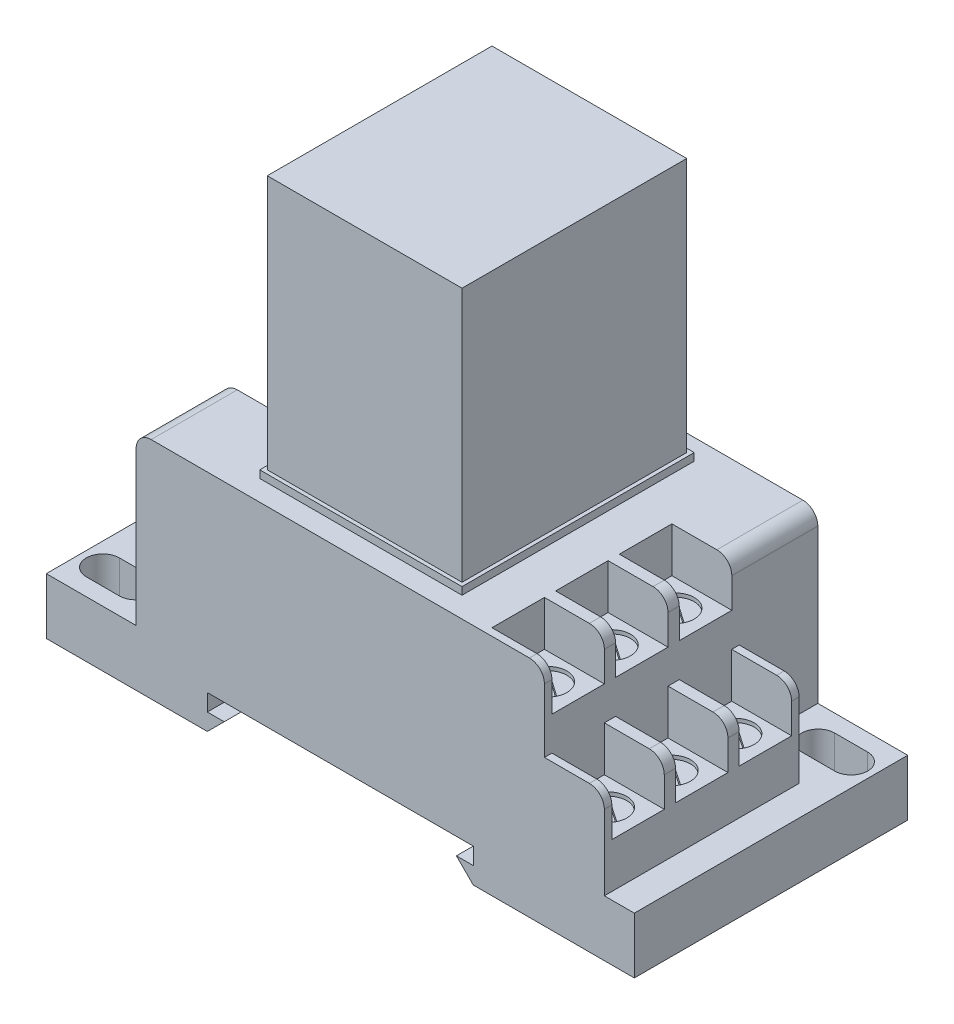
SolidWorks part; units mm, degrees
ref_plane "Спереди" through (0, 0, 0) normal (0, 0, 1) x (1, 0, 0)
ref_plane "Сверху" through (0, 0, 0) normal (0, 1, 0) x (1, 0, 0)
ref_plane "Справа" through (0, 0, 0) normal (1, 0, 0) x (0, 0, -1)
sketch "Эскиз1" plane through (0, 0, 0) normal (0, 1, 0) x (1, 0, 0)
  line L1 (0, 0) -> (78.5, 0)
  line L2 (0, 0) -> (0, 36.5)
  line L3 (0, 36.5) -> (78.5, 36.5)
  line L4 (78.5, 0) -> (78.5, 36.5)
  dimension "D1" = 36.5
  dimension "D2" = 78.5
extrude "Бобышка-Вытянуть1" add sketch "Эскиз1" along normal blind 30
sketch "Эскиз2" plane through (0, 0, 0) normal (0, 0, 1) x (1, 0, 0)
  line L0 (39.25, 30) -> (39.25, 0) construction
  line L1 (21.5, 4.5) -> (57, 4.5)
  line L2 (21.5, 4.5) -> (21.5, 2.25)
  line L4 (0, 0) -> (78.5, 0) construction
  line L5 (57, 4.5) -> (57, 2.25)
  line L6 (21.5, 2.25) -> (23.75, 2.25)
  line L7 (23.75, 2.25) -> (21.5, 0)
  line L8 (0, 30) -> (78.5, 30) construction
  line L9 (54.75, 2.25) -> (57, 0)
  line L10 (57, 2.25) -> (54.75, 2.25)
  line L11 (21.5, 0) -> (57, 0)
  dimension "D1" = 35.5
  dimension "D2" = 4.5
  dimension "D3" = 17.75
  dimension "D4" = 2.25
  dimension "D5" = 2.25
  dimension "D6" = 17.75
extrude "Вырез-Вытянуть1" cut sketch "Эскиз2" against normal through all
sketch "Эскиз3" plane through (0, 0, 0) normal (0, 0, 1) x (1, 0, 0)
  line L0 (0, 7.5) -> (12, 7.5)
  line L1 (0, 30) -> (0, 0) construction
  line L2 (12, 7.5) -> (12, 28)
  line L3 (0, 30) -> (78.5, 30) construction
  line L4 (14, 30) -> (64.5, 30)
  line L5 (66.5, 28) -> (66.5, 7.5)
  line L6 (66.5, 7.5) -> (78.5, 7.5)
  line L7 (78.5, 30) -> (78.5, 0) construction
  line L8 (78.5, 7.5) -> (78.5, 31.9767)
  line L9 (78.5, 31.9767) -> (0, 31.9767)
  line L10 (0, 31.9767) -> (0, 7.5)
  line L11 (0, 0) -> (21.5, 0) construction
  line L12 (57, 0) -> (78.5, 0) construction
  arc A0 (14, 30) -> (12, 28) centre (14, 28) ccw
  arc A1 (66.5, 28) -> (64.5, 30) centre (64.5, 28) ccw
  point P22 (12, 30)
  point P25 (66.5, 30)
  dimension "D5" = 2
  dimension "D6" = 2
  dimension "D1" = 7.5
  dimension "D2" = 12
  dimension "D3" = 7.5
  dimension "D4" = 12
extrude "Вырез-Вытянуть2" cut sketch "Эскиз3" against normal through all
sketch "Эскиз4" plane through (0, 0, 0) normal (0, 0, 1) x (1, 0, 0)
  line L1 (66.5, 28) -> (66.5, 7.5) construction
  line L2 (66.5, 7.5) -> (74.5, 7.5)
  line L3 (66.5, 7.5) -> (66.5, 19.5)
  line L4 (66.5, 19.5) -> (72.5, 19.5)
  line L6 (74.5, 7.5) -> (74.5, 17.5)
  line L7 (66.5, 7.5) -> (78.5, 7.5) construction
  arc A0 (74.5, 17.5) -> (72.5, 19.5) centre (72.5, 17.5) ccw
  point P10 (74.5, 19.5)
  dimension "D3" = 2
  dimension "D1" = 8
  dimension "D2" = 12
extrude "Бобышка-Вытянуть2" add sketch "Эскиз4" against normal blind 26 separate body
sketch "Эскиз6" plane through (0, 0, -36.5) normal (0, 0, -1) x (-1, 0, 0)
  line L0 (0, 7.5) -> (-12, 7.5) construction
  line L1 (-12, 7.5) -> (-4, 7.5)
  line L2 (-12, 7.5) -> (-12, 19.5)
  line L3 (-12, 19.5) -> (-6, 19.5)
  line L4 (-4, 7.5) -> (-4, 17.5)
  arc A0 (-4, 17.5) -> (-6, 19.5) centre (-6, 17.5) ccw
  point P8 (-4, 19.5)
  dimension "D3" = 2
  dimension "D1" = 8
  dimension "D2" = 12
extrude "Бобышка-Вытянуть6" add sketch "Эскиз6" against normal blind 26 separate body
sketch "Эскиз7" plane through (0, 7.5, 0) normal (0, 1, 0) x (1, 0, 0)
  line L0 (71.05, 32) -> (75.45, 32) construction
  line L1 (71.05, 34.2) -> (75.45, 34.2)
  line L2 (71.05, 29.8) -> (75.45, 29.8)
  line L3 (3.05, 4.5) -> (7.45, 4.5) construction
  line L4 (3.05, 6.7) -> (7.45, 6.7)
  line L5 (3.05, 2.3) -> (7.45, 2.3)
  line L6 (0, 18.25) -> (78.5, 18.25) construction
  line L7 (0, 36.5) -> (0, 0) construction
  line L8 (78.5, 36.5) -> (78.5, 0) construction
  line L9 (39.25, 36.5) -> (39.25, 0) construction
  line L10 (64.5, 36.5) -> (14, 36.5) construction
  line L11 (14, 0) -> (64.5, 0) construction
  arc A0 (71.05, 34.2) -> (71.05, 29.8) centre (71.05, 32) ccw
  arc A1 (75.45, 29.8) -> (75.45, 34.2) centre (75.45, 32) ccw
  arc A2 (3.05, 6.7) -> (3.05, 2.3) centre (3.05, 4.5) ccw
  arc A3 (7.45, 2.3) -> (7.45, 6.7) centre (7.45, 4.5) ccw
  point P2 (73.25, 32)
  point P7 (5.25, 4.5)
  dimension "D1" = 13.75
  dimension "D2" = 27.5
  dimension "D3" = 4.4
  dimension "D4" = 4.4
  dimension "D5" = 68
  dimension "D6" = 34
  dimension "D7" = 4.4
  dimension "D8" = 4.4
extrude "Вырез-Вытянуть3" cut sketch "Эскиз7" against normal up to next (7.5 mm away)
sketch "Эскиз8" plane through (0, 19.5, 0) normal (0, 1, 0) x (1, 0, 0)
  line L2 (4, 10.5) -> (4, 36.5) construction
  line L4 (6, 10.5) -> (12, 10.5) construction
  line L11 (4, 18.5) -> (12, 18.5)
  line L12 (4, 18.5) -> (4, 11.5)
  line L13 (4, 11.5) -> (12, 11.5)
  line L14 (12, 18.5) -> (12, 11.5)
  line L17 (4, 20) -> (12, 20)
  line L18 (4, 27) -> (4, 20)
  line L19 (4, 27) -> (12, 27)
  line L20 (12, 27) -> (12, 20)
  line L21 (4, 28.5) -> (12, 28.5)
  line L22 (4, 35.5) -> (4, 28.5)
  line L23 (4, 35.5) -> (12, 35.5)
  line L24 (12, 35.5) -> (12, 28.5)
  dimension "D1" = 1
  dimension "D2" = 3
  dimension "D3" = 7
  dimension "D4" = 8
  dimension "D5" = 8
extrude "Вырез-Вытянуть4" cut sketch "Эскиз8" against normal blind 6
sketch "Эскиз9" plane through (0, 19.5, 0) normal (0, 1, 0) x (1, 0, 0)
  line L0 (66.5, 26) -> (66.5, 0) construction
  line L1 (66.5, 25) -> (74.5, 25)
  line L2 (66.5, 25) -> (66.5, 18)
  line L3 (66.5, 18) -> (74.5, 18)
  line L4 (74.5, 25) -> (74.5, 18)
  line L5 (74.5, 26) -> (74.5, 0) construction
  line L6 (72.5, 26) -> (66.5, 26) construction
  line L7 (74.5, 16.5) -> (74.5, 9.5)
  line L8 (66.5, 16.5) -> (74.5, 16.5)
  line L9 (66.5, 16.5) -> (66.5, 9.5)
  line L10 (66.5, 9.5) -> (74.5, 9.5)
  line L11 (74.5, 8) -> (74.5, 1)
  line L12 (66.5, 8) -> (74.5, 8)
  line L21 (66.5, 8) -> (66.5, 1)
  line L22 (66.5, 1) -> (74.5, 1)
  dimension "D1" = 7
  dimension "D2" = 1
  dimension "D4" = 3
extrude "Вырез-Вытянуть5" cut sketch "Эскиз9" against normal blind 6
sketch "Эскиз10" plane through (0, 30, 0) normal (0, 1, 0) x (1, 0, 0)
  line L0 (39.25, 36.5) -> (39.25, 0) construction
  line L1 (64.5, 36.5) -> (14, 36.5) construction
  line L2 (14, 0) -> (64.5, 0) construction
  line L3 (14, 18.25) -> (64.5, 18.25) construction
  line L4 (14, 36.5) -> (14, 0) construction
  line L5 (64.5, 36.5) -> (64.5, 0) construction
  line L7 (25.75, 33.75) -> (52.75, 33.75)
  line L8 (25.75, 33.75) -> (25.75, 2.75)
  line L9 (25.75, 2.75) -> (52.75, 2.75)
  line L10 (52.75, 33.75) -> (52.75, 2.75)
  dimension "D1" = 27
  dimension "D2" = 13.5
  dimension "D3" = 31
  dimension "D4" = 15.5
extrude "Бобышка-Вытянуть7" add sketch "Эскиз10" along normal blind 35
sketch "Эскиз11" plane through (0, 65, 0) normal (0, 1, 0) x (1, 0, 0)
  line L0 (25.75, 33.75) -> (25.75, 2.75) construction
  line L1 (26.25, 33.25) -> (52.25, 33.25)
  line L2 (26.25, 33.25) -> (26.25, 3.25)
  line L3 (26.25, 3.25) -> (52.25, 3.25)
  line L4 (52.25, 33.25) -> (52.25, 3.25)
  line L5 (52.75, 33.75) -> (25.75, 33.75) construction
  line L6 (52.75, 2.75) -> (52.75, 33.75) construction
  line L7 (25.75, 2.75) -> (52.75, 2.75) construction
  line L9 (25.75, 33.75) -> (52.75, 33.75)
  line L10 (25.75, 33.75) -> (25.75, 2.75)
  line L11 (25.75, 2.75) -> (52.75, 2.75)
  line L12 (52.75, 33.75) -> (52.75, 2.75)
  dimension "D1" = 0.5
  dimension "D2" = 0.5
  dimension "D3" = 0.5
  dimension "D4" = 0.5
extrude "Вырез-Вытянуть6" cut sketch "Эскиз11" against normal blind 34
sketch "Эскиз12" plane through (0, 30, 0) normal (0, 1, 0) x (1, 0, 0)
  line L0 (12, 28.5) -> (12, 35.5) construction
  line L1 (12, 35.5) -> (20, 35.5)
  line L2 (12, 35.5) -> (12, 28.5)
  line L3 (12, 28.5) -> (20, 28.5)
  line L4 (20, 35.5) -> (20, 28.5)
  line L5 (64.5, 36.5) -> (14, 36.5) construction
  line L6 (12, 20) -> (20, 20)
  line L7 (12, 27) -> (20, 27)
  line L8 (20, 27) -> (20, 20)
  line L9 (12, 27) -> (12, 20)
  line L10 (12, 11.5) -> (20, 11.5)
  line L11 (12, 18.5) -> (20, 18.5)
  line L12 (20, 18.5) -> (20, 11.5)
  line L13 (12, 18.5) -> (12, 11.5)
  line L14 (58.5, 8) -> (66.5, 8)
  line L15 (58.5, 25.0174) -> (58.5, 18)
  line L16 (58.5, 1) -> (66.5, 1)
  line L17 (58.5, 8) -> (58.5, 1)
  line L18 (58.5, 25.0174) -> (66.5, 25.0174)
  line L19 (66.5, 16.5) -> (66.5, 9.5)
  line L20 (58.5, 16.5) -> (58.5, 9.5)
  line L21 (66.5, 25.0174) -> (66.5, 18)
  line L22 (66.5, 8) -> (66.5, 1)
  line L23 (58.5, 18) -> (66.5, 18)
  line L24 (58.5, 9.5) -> (66.5, 9.5)
  line L25 (58.5, 16.5) -> (66.5, 16.5)
  line L26 (14, 0) -> (64.5, 0) construction
  line L27 (66.5, 36.5) -> (66.5, 0) construction
  dimension "D1" = 7
  dimension "D2" = 8
  dimension "D3" = 8
  dimension "D4" = 1
  dimension "D6" = 1
  dimension "D7" = 8
  dimension "D8" = 8
  dimension "D9" = 8
  dimension "D10" = 8
  dimension "D11" = 8
  dimension "D12" = 7
  dimension "D13" = 7
  dimension "D14" = 1.5
  dimension "D15" = 1.5
  dimension "D5" = 3
extrude "Вырез-Вытянуть7" cut sketch "Эскиз12" against normal blind 6
sketch "Эскиз13" plane through (0, 13.5, 0) normal (0, 1, 0) x (1, 0, 0)
  line L0 (4, 35.5) -> (4, 28.5) construction
  line L1 (12, 35.5) -> (4, 35.5) construction
  line L2 (66.5, 1) -> (74.5, 1) construction
  line L3 (74.5, 1) -> (74.5, 8) construction
  line L4 (74.5, 9.5) -> (74.5, 16.5) construction
  line L5 (66.5, 9.5) -> (74.5, 9.5) construction
  line L6 (66.5, 18) -> (74.5, 18) construction
  line L7 (74.5, 18) -> (74.5, 25) construction
  circle A0 centre (8, 32) radius 2.5
  circle A1 centre (8, 23.5) radius 2.5
  circle A2 centre (8, 15) radius 2.5
  circle A3 centre (70.5, 4.5) radius 2.5
  circle A4 centre (70.5, 21.5) radius 2.5
  circle A5 centre (70.5, 13) radius 2.5
  dimension "D1" = 4
  dimension "D2" = 3.5
  dimension "D3" = 5
  dimension "D5" = 5
  dimension "D6" = 3.5
  dimension "D7" = 4
  dimension "D8" = 4
  dimension "D9" = 3.5
  dimension "D10" = 3.5
  dimension "D11" = 4
  dimension "D4" = 3
extrude "Вырез-Вытянуть8" cut sketch "Эскиз13" against normal blind 1
sketch "Эскиз14" plane through (0, 12.5, 0) normal (0, 1, 0) x (1, 0, 0)
  line L0 (68.1956, 5.4693) -> (72.2402, 2.7051)
  line L1 (68.7598, 6.2949) -> (72.8044, 3.5307)
  line L2 (68.7598, 14.7949) -> (72.8044, 12.0307)
  line L3 (68.1956, 13.9693) -> (72.2402, 11.2051)
  line L4 (68.7598, 23.2949) -> (72.8044, 20.5307)
  line L5 (68.1956, 22.4693) -> (72.2402, 19.7051)
  line L6 (5.6956, 24.4693) -> (9.7402, 21.7051)
  line L7 (6.2598, 16.7949) -> (10.3044, 14.0307)
  line L8 (6.2598, 25.2949) -> (10.3044, 22.5307)
  line L9 (5.6956, 32.9693) -> (9.7402, 30.2051)
  line L10 (5.6956, 15.9693) -> (9.7402, 13.2051)
  line L11 (6.2598, 33.7949) -> (10.3044, 31.0307)
  circle A0 centre (70.5, 4.5) radius 2.5 construction
  circle A1 centre (70.5, 4.5) radius 2.5 construction
  arc A2 (68.7598, 6.2949) -> (72.8044, 3.5307) centre (70.5, 4.5) cw
  arc A3 (68.1956, 5.4693) -> (72.2402, 2.7051) centre (70.5, 4.5) ccw
  arc A4 (68.7598, 14.7949) -> (72.8044, 12.0307) centre (70.5, 13) cw
  arc A5 (68.1956, 13.9693) -> (72.2402, 11.2051) centre (70.5, 13) ccw
  arc A6 (68.7598, 23.2949) -> (72.8044, 20.5307) centre (70.5, 21.5) cw
  arc A7 (68.1956, 22.4693) -> (72.2402, 19.7051) centre (70.5, 21.5) ccw
  arc A8 (5.6956, 24.4693) -> (9.7402, 21.7051) centre (8, 23.5) ccw
  arc A9 (6.2598, 16.7949) -> (10.3044, 14.0307) centre (8, 15) cw
  arc A10 (6.2598, 25.2949) -> (10.3044, 22.5307) centre (8, 23.5) cw
  arc A11 (6.2598, 33.7949) -> (10.3044, 31.0307) centre (8, 32) cw
  arc A12 (5.6956, 15.9693) -> (9.7402, 13.2051) centre (8, 15) ccw
  arc A13 (5.6956, 32.9693) -> (9.7402, 30.2051) centre (8, 32) ccw
  dimension "D1" = 0.5
  dimension "D2" = 1
  dimension "D4" = 1
  dimension "D3" = 3
extrude "Бобышка-Вытянуть8" add sketch "Эскиз14" along normal blind 0.5
sketch "Эскиз15" plane through (0, 24, 0) normal (0, 1, 0) x (1, 0, 0)
  line L0 (20, 35.5) -> (12, 35.5) construction
  line L1 (20, 28.5) -> (20, 35.5) construction
  line L2 (58.5, 8) -> (58.5, 1) construction
  line L3 (58.5, 1) -> (64.5, 1) construction
  line L4 (58.5, 16.5) -> (58.5, 9.5) construction
  line L5 (58.5, 25.0174) -> (58.5, 18) construction
  circle A0 centre (16, 32) radius 2.5
  circle A1 centre (16, 23.5) radius 2.5
  circle A2 centre (16, 15) radius 2.5
  circle A3 centre (62.5, 13) radius 2.5
  circle A4 centre (62.5, 21.5) radius 2.5
  circle A5 centre (62.5, 4.5) radius 2.5
  point P2 (16, 35.5)
  dimension "D1" = 5
  dimension "D2" = 3.5
  dimension "D3" = 4
  dimension "D5" = 5
  dimension "D6" = 4
  dimension "D8" = 8.5
  dimension "D9" = 8.5
  dimension "D10" = 4
  dimension "D11" = 4
  dimension "D7" = 3.5
  dimension "D4" = 3
extrude "Вырез-Вытянуть9" cut sketch "Эскиз15" against normal blind 1
sketch "Эскиз16" plane through (0, 23, 0) normal (0, 1, 0) x (1, 0, 0)
  line L0 (13.7032, 32.9873) -> (17.7261, 30.1915)
  line L1 (14.2739, 33.8085) -> (18.2968, 31.0127)
  line L2 (13.7032, 24.4873) -> (17.7261, 21.6915)
  line L3 (14.2739, 25.3085) -> (18.2968, 22.5127)
  line L4 (13.7032, 15.9873) -> (17.7261, 13.1915)
  line L5 (14.2739, 16.8085) -> (18.2968, 14.0127)
  line L6 (60.7739, 6.3085) -> (64.7968, 3.5127)
  line L7 (60.7739, 14.8085) -> (64.7968, 12.0127)
  line L8 (60.2032, 13.9873) -> (64.2261, 11.1915)
  line L9 (60.7739, 23.3085) -> (64.7968, 20.5127)
  line L10 (60.2032, 5.4873) -> (64.2261, 2.6915)
  line L11 (60.2032, 22.4873) -> (64.2261, 19.6915)
  circle A0 centre (16, 32) radius 2.5 construction
  arc A1 (14.2739, 33.8085) -> (18.2968, 31.0127) centre (16, 32) cw
  circle A2 centre (16, 32) radius 2.5 construction
  arc A3 (13.7032, 32.9873) -> (17.7261, 30.1915) centre (16, 32) ccw
  arc A4 (13.7032, 24.4873) -> (17.7261, 21.6915) centre (16, 23.5) ccw
  arc A5 (14.2739, 25.3085) -> (18.2968, 22.5127) centre (16, 23.5) cw
  arc A6 (13.7032, 15.9873) -> (17.7261, 13.1915) centre (16, 15) ccw
  arc A7 (14.2739, 16.8085) -> (18.2968, 14.0127) centre (16, 15) cw
  arc A8 (60.2032, 13.9873) -> (64.2261, 11.1915) centre (62.5, 13) ccw
  arc A9 (60.2032, 22.4873) -> (64.2261, 19.6915) centre (62.5, 21.5) ccw
  arc A10 (60.7739, 14.8085) -> (64.7968, 12.0127) centre (62.5, 13) cw
  arc A11 (60.7739, 23.3085) -> (64.7968, 20.5127) centre (62.5, 21.5) cw
  arc A12 (60.7739, 6.3085) -> (64.7968, 3.5127) centre (62.5, 4.5) cw
  arc A13 (60.2032, 5.4873) -> (64.2261, 2.6915) centre (62.5, 4.5) ccw
  dimension "D1" = 0.5
  dimension "D2" = 1
  dimension "D4" = 1
  dimension "D3" = 3
extrude "Бобышка-Вытянуть9" add sketch "Эскиз16" along normal blind 0.5
